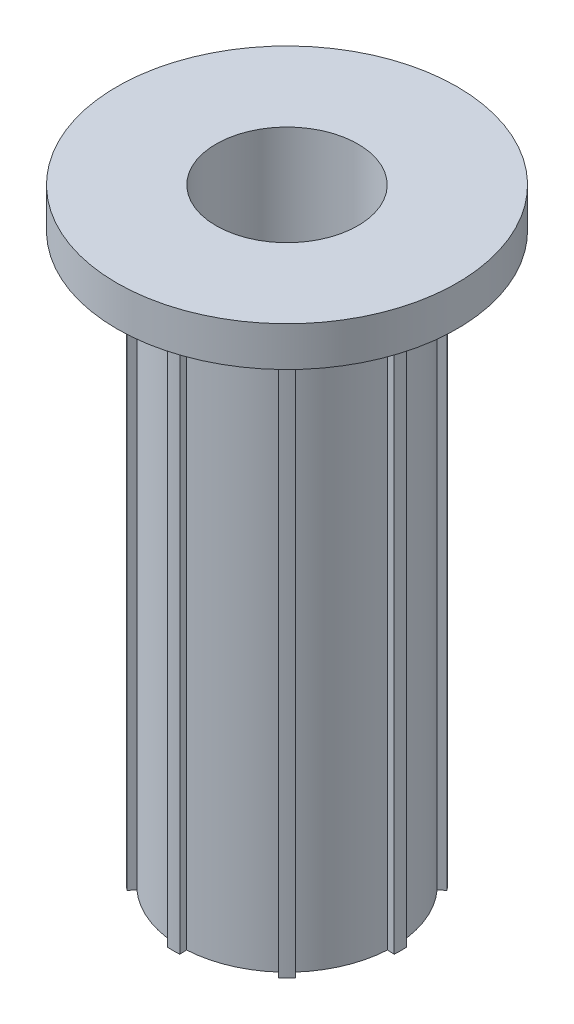
SolidWorks part; units mm, degrees
material "Nylon 6/10"
ref_plane "Front Plane" through (0, 0, 0) normal (0, 0, 1) x (1, 0, 0)
ref_plane "Top Plane" through (0, 0, 0) normal (0, 1, 0) x (1, 0, 0)
ref_plane "Right Plane" through (0, 0, 0) normal (1, 0, 0) x (0, 0, -1)
sketch "Sketch2" plane through (0, 0, 0) normal (0, 1, 0) x (1, 0, 0)
  circle A0 centre (0, 0) radius 5.08
  dimension "D1" = 10.16
extrude "Boss-Extrude1" add sketch "Sketch2" along normal blind 25.4
sketch "Sketch3" plane through (0, 0, 0) normal (0, -1, 0) x (1, 0, 0)
  line L1 (-7.0848, -6.3664) -> (-7.5344, -6.816)
  line L2 (-10.1473, -0.508) -> (-9.5114, -0.508)
  line L3 (-0.508, 10.1473) -> (-0.508, 9.5114)
  line L4 (-10.1473, 0.508) -> (-9.5114, 0.508)
  line L5 (0.508, 10.1473) -> (0.508, 9.5114)
  line L6 (-7.5344, 6.816) -> (-7.0848, 6.3664)
  line L7 (-6.3664, -7.0848) -> (-6.816, -7.5344)
  line L8 (-0.508, -9.5114) -> (-0.508, -10.1473)
  line L9 (6.816, 7.5344) -> (6.3664, 7.0848)
  line L10 (-6.816, 7.5344) -> (-6.3664, 7.0848)
  line L11 (7.5344, 6.816) -> (7.0848, 6.3664)
  line L12 (0.508, -9.5114) -> (0.508, -10.1473)
  line L13 (6.3664, -7.0848) -> (6.816, -7.5344)
  line L14 (7.0848, -6.3664) -> (7.5344, -6.816)
  line L15 (9.5114, -0.508) -> (10.1473, -0.508)
  line L16 (9.5114, 0.508) -> (10.1473, 0.508)
  arc A0 (-9.5114, -0.508) -> (-7.0848, -6.3664) centre (0, 0) ccw
  arc A1 (-7.0848, 6.3664) -> (-9.5114, 0.508) centre (0, 0) ccw
  arc A2 (-10.1473, -0.508) -> (-7.5344, -6.816) centre (0, 0) ccw
  arc A3 (-7.5344, 6.816) -> (-10.1473, 0.508) centre (0, 0) ccw
  arc A4 (-0.508, 9.5114) -> (-6.3664, 7.0848) centre (0, 0) ccw
  arc A5 (-0.508, 10.1473) -> (-6.816, 7.5344) centre (0, 0) ccw
  arc A6 (6.3664, 7.0848) -> (0.508, 9.5114) centre (0, 0) ccw
  arc A7 (6.816, 7.5344) -> (0.508, 10.1473) centre (0, 0) ccw
  arc A8 (9.5114, 0.508) -> (7.0848, 6.3664) centre (0, 0) ccw
  arc A9 (10.1473, 0.508) -> (7.5344, 6.816) centre (0, 0) ccw
  arc A10 (7.0848, -6.3664) -> (9.5114, -0.508) centre (0, 0) ccw
  arc A11 (7.5344, -6.816) -> (10.1473, -0.508) centre (0, 0) ccw
  arc A12 (0.508, -9.5114) -> (6.3664, -7.0848) centre (0, 0) ccw
  arc A13 (0.508, -10.1473) -> (6.816, -7.5344) centre (0, 0) ccw
  arc A14 (-6.3664, -7.0848) -> (-0.508, -9.5114) centre (0, 0) ccw
  arc A15 (-6.816, -7.5344) -> (-0.508, -10.1473) centre (0, 0) ccw
sketch "Sketch4" plane through (0, 25.4, 0) normal (0, 1, 0) x (1, 0, 0)
  circle A0 centre (0, 0) radius 7.62
  dimension "D1" = 15.24
extrude "Boss-Extrude2" add sketch "Sketch4" along normal blind 1.778
sketch "Sketch5" plane through (0, 27.178, 0) normal (0, 1, 0) x (1, 0, 0)
  circle A0 centre (0, 0) radius 3.175
  dimension "D1" = 6.35
extrude "Cut-Extrude2" cut sketch "Sketch5" against normal through all
sketch "Sketch6" plane through (0, 0, 0) normal (0, -1, 0) x (1, 0, 0)
  line L0 (-3.7786, 3.3954) -> (-3.5424, 3.1832)
  line L1 (-0.2709, 5.0728) -> (-0.254, 4.7557)
  line L2 (-3.3954, 3.7786) -> (-3.1832, 3.5424)
  line L3 (0.2709, 5.0728) -> (0.254, 4.7557)
  line L4 (3.3954, 3.7786) -> (3.1832, 3.5424)
  line L5 (3.7786, 3.3954) -> (3.5424, 3.1832)
  line L6 (5.0728, 0.2709) -> (4.7557, 0.254)
  line L7 (5.0728, -0.2709) -> (4.7557, -0.254)
  line L8 (3.1832, -3.5424) -> (3.3954, -3.7786)
  line L9 (3.5424, -3.1832) -> (3.7786, -3.3954)
  line L10 (-4.7557, 0.254) -> (-5.0728, 0.2709)
  line L11 (-4.7557, -0.254) -> (-5.0728, -0.2709)
  line L12 (-3.5424, -3.1832) -> (-3.7786, -3.3954)
  line L13 (-3.1832, -3.5424) -> (-3.3954, -3.7786)
  line L14 (-0.254, -4.7557) -> (-0.2709, -5.0728)
  line L15 (0.254, -4.7557) -> (0.2709, -5.0728)
  arc A0 (-3.5424, 3.1832) -> (-4.7557, 0.254) centre (0, 0) ccw
  arc A1 (-3.7786, 3.3954) -> (-5.0728, 0.2709) centre (0, 0) ccw
  arc A2 (-0.2709, 5.0728) -> (-3.3954, 3.7786) centre (0, 0) ccw
  arc A3 (-0.254, 4.7557) -> (-3.1832, 3.5424) centre (0, 0) ccw
  arc A4 (0.2709, -5.0728) -> (3.3954, -3.7786) centre (0, 0) ccw
  arc A5 (0.254, -4.7557) -> (3.1832, -3.5424) centre (0, 0) ccw
  arc A6 (-3.3954, -3.7786) -> (-0.2709, -5.0728) centre (0, 0) ccw
  arc A7 (-3.1832, -3.5424) -> (-0.254, -4.7557) centre (0, 0) ccw
  arc A8 (-5.0728, -0.2709) -> (-3.7786, -3.3954) centre (0, 0) ccw
  arc A9 (-4.7557, -0.254) -> (-3.5424, -3.1832) centre (0, 0) ccw
  arc A10 (3.7786, -3.3954) -> (5.0728, -0.2709) centre (0, 0) ccw
  arc A11 (3.5424, -3.1832) -> (4.7557, -0.254) centre (0, 0) ccw
  arc A12 (5.0728, 0.2709) -> (3.7786, 3.3954) centre (0, 0) ccw
  arc A13 (4.7557, 0.254) -> (3.5424, 3.1832) centre (0, 0) ccw
  arc A14 (3.3954, 3.7786) -> (0.2709, 5.0728) centre (0, 0) ccw
  arc A15 (3.1832, 3.5424) -> (0.254, 4.7557) centre (0, 0) ccw
  dimension "D1" = 9.525
extrude "Cut-Extrude3" cut sketch "Sketch6" against normal blind 25.4
